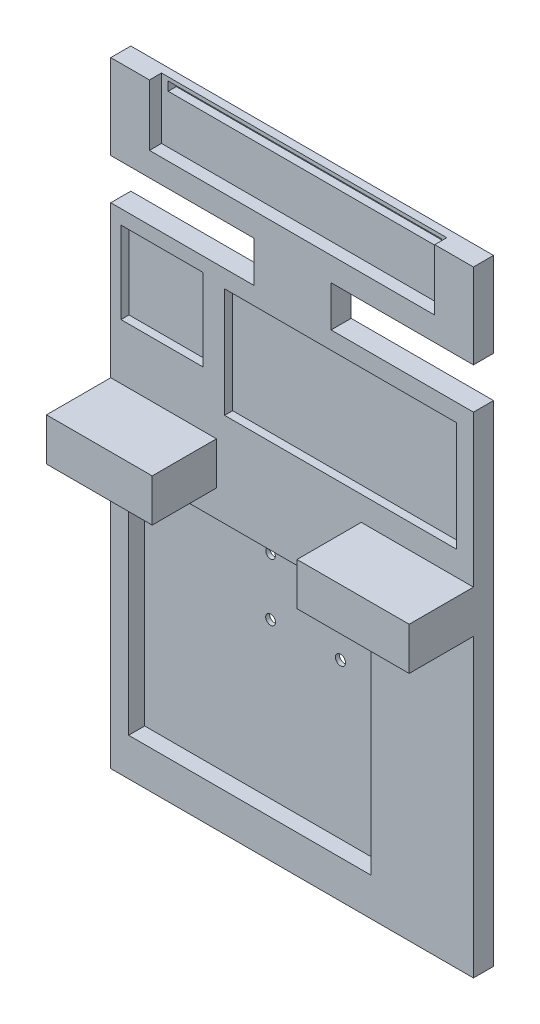
SolidWorks part; units mm, degrees
ref_plane "Plano frontal" through (0, 0, 0) normal (0, 0, 1) x (1, 0, 0)
ref_plane "Plano superior" through (0, 0, 0) normal (0, 1, 0) x (1, 0, 0)
ref_plane "Plano direito" through (0, 0, 0) normal (1, 0, 0) x (0, 0, -1)
sketch "Esboço1" plane through (0, 0, 0) normal (0, 0, 1) x (1, 0, 0)
  line L0 (-44.6735, 40.7151) -> (-44.6735, 19.6036)
  line L1 (-44.6735, 40.7151) -> (45.616, 40.7151)
  line L2 (45.616, 40.7151) -> (45.616, 19.6036)
  line L3 (-44.6735, 19.6036) -> (-9.0478, 19.6036)
  line L4 (45.616, 19.6036) -> (10.1788, 19.6036)
  line L5 (10.1788, 19.6036) -> (10.1788, 9.4248)
  line L6 (-9.0478, 19.6036) -> (-9.0478, 9.4248)
  line L7 (-9.0478, 9.4248) -> (-44.6735, 9.4248)
  line L8 (10.1788, 9.4248) -> (45.616, 9.4248)
  line L9 (-44.6735, 9.4248) -> (-44.6735, -71.4399)
  line L10 (-44.6735, -71.4399) -> (45.616, -71.4399)
  line L11 (45.616, -71.4399) -> (45.616, 9.4248)
extrude "base" add sketch "Esboço1" along normal blind 5
sketch "Esboço2" plane through (0, 0, 5) normal (0, 0, 1) x (1, 0, 0)
  line L0 (-35.0374, 25.5264) -> (35.9799, 25.5264)
  line L1 (45.616, 40.7151) -> (-44.6735, 40.7151) construction
  line L2 (-35.0374, 40.7151) -> (35.9799, 40.7151)
  line L4 (35.9799, 25.5264) -> (35.9799, 40.7151)
  line L5 (-35.0374, 25.5264) -> (-35.0374, 40.7151)
extrude "sensor" cut sketch "Esboço2" against normal blind 3
ref_plane "Plano1" through (-35.0374, 40.7151, 5) normal (0, -1, 0) x (-1, 0, 0)
ref_plane "Plano2" through (-44.6735, -71.4399, 5) normal (0, -1, 0) x (-1, 0, 0)
other "extensão base" face at (0.4712, -71.4399, 2.5) parameters "D1"=41.1249
sketch "Esboço3" plane through (0, 0, 2) normal (0, 0, 1) x (1, 0, 0)
  line L0 (34.723, 39.8114) -> (-33.3668, 39.8114)
  line L3 (-33.3668, 39.8114) -> (-33.3668, 37.6066)
  line L4 (-33.3668, 37.6066) -> (34.723, 37.6066)
  line L5 (34.723, 37.6066) -> (34.723, 39.8114)
extrude "\"furo\" sensor" cut sketch "Esboço3" against normal blind 10 contours L3 L4 L5 L0
sketch "Esboço5" plane through (0, 0, 0) normal (0, 0, -1) x (-1, 0, 0)
  line L0 (-10.1084, -65.8553) -> (10.4374, -65.8553)
  line L3 (10.4374, -65.8553) -> (10.4374, -48.8461)
  line L5 (10.4374, -48.8461) -> (-10.1084, -48.8461)
  line L6 (-10.1084, -48.8461) -> (-10.1084, -65.8553)
  circle A0 centre (-8.5176, -50.2919) radius 1.1882
  circle A1 centre (-8.5176, -64.5501) radius 1.2581
  circle A2 centre (8.8858, -64.5501) radius 1.2206
  circle A3 centre (8.8858, -50.2919) radius 1.1882
extrude "conector roda bamba" cut sketch "Esboço5" against normal blind 10 contours A0 | A3 | A1 | A2
sketch "Esboço8" plane through (0, 0, 5) normal (0, 0, 1) x (1, 0, 0)
  line L0 (-42.128, 5.8866) -> (-21.7506, 5.8866)
  line L1 (-21.7506, 5.8866) -> (-21.7506, -14.4908)
  line L2 (-21.7506, -14.4908) -> (-42.128, -14.4908)
  line L3 (-42.128, -14.4908) -> (-42.128, 5.8866)
extrude "ponte H" cut sketch "Esboço8" against normal blind 2
sketch "Esboço10" plane through (0, 0, 5) normal (0, 0, 1) x (1, 0, 0)
  line L0 (-16.3317, 5.0446) -> (41.4323, 5.0446)
  line L1 (41.4323, 5.0446) -> (41.4323, -22.2375)
  line L2 (41.4323, -22.2375) -> (-16.3317, -22.2375)
  line L3 (-16.3317, -22.2375) -> (-16.3317, 5.0446)
extrude "esp" cut sketch "Esboço10" against normal blind 2
sketch "Esboço11" plane through (0, 0, 5) normal (0, 0, 1) x (1, 0, 0)
  line L0 (45.616, -28.3002) -> (17.6868, -28.3002)
  line L1 (45.616, -112.5648) -> (45.616, 9.4248) construction
  line L2 (17.6868, -28.3002) -> (17.6868, -38.91)
  line L3 (17.6868, -38.91) -> (45.616, -38.91)
  line L4 (45.616, -38.91) -> (45.616, -28.3002)
  line L5 (-44.6735, -28.3002) -> (-18.3526, -28.3002)
  line L6 (-44.6735, 9.4248) -> (-44.6735, -112.5648) construction
  line L7 (-18.3526, -28.3002) -> (-18.3526, -38.91)
  line L8 (-18.3526, -38.91) -> (-44.6735, -38.91)
  line L9 (-44.6735, -38.91) -> (-44.6735, -28.3002)
extrude "Ressalto-extrusão2" add sketch "Esboço11" along normal blind 16
sketch "Esboço13" plane through (0, 0, 5) normal (0, 0, 1) x (1, 0, 0)
  line L0 (-40.2198, -45.5887) -> (20.0737, -45.5887)
  line L1 (20.0737, -45.5887) -> (20.0737, -103.1512)
  line L2 (-40.2198, -45.5887) -> (-40.2198, -103.1512)
  line L3 (-40.2198, -103.1512) -> (20.0737, -103.1512)
extrude "Corte-extrusão12" cut sketch "Esboço13" against normal blind 4
